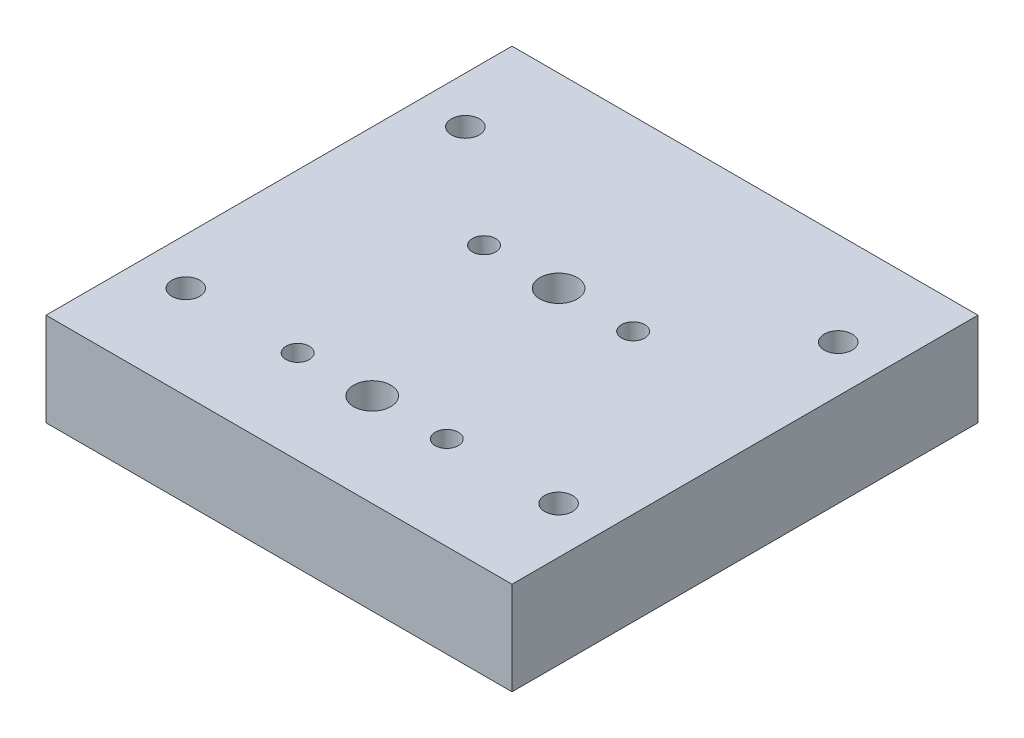
SolidWorks part; units mm, degrees
material "Сосна"
ref_plane "Спереди" through (0, 0, 0) normal (0, 0, 1) x (1, 0, 0)
ref_plane "Сверху" through (0, 0, 0) normal (0, 1, 0) x (1, 0, 0)
ref_plane "Справа" through (0, 0, 0) normal (1, 0, 0) x (0, 0, -1)
sketch "Эскиз1" plane through (0, 0, 0) normal (0, 1, 0) x (1, 0, 0)
  line L1 (0, 0) -> (100, 0)
  line L2 (0, 0) -> (0, 100)
  line L3 (0, 100) -> (100, 100)
  line L4 (100, 0) -> (100, 100)
  dimension "D1" = 100
  dimension "D2" = 100
extrude "Бобышка-Вытянуть1" add sketch "Эскиз1" along normal blind 20
sketch "Эскиз2" plane through (0, 20, 0) normal (0, 1, 0) x (1, 0, 0)
  line L0 (10, 100) -> (10, 0) construction
  line L1 (100, 100) -> (0, 100) construction
  line L2 (0, 0) -> (100, 0) construction
  line L3 (90, 100) -> (90, 0) construction
  line L4 (50, 100) -> (50, 0) construction
  line L5 (0, 100) -> (0, 0) construction
  line L6 (100, 0) -> (100, 100) construction
  line L7 (28.3008, 20) -> (77.5601, 20) construction
  line L8 (24.6726, 60) -> (70.7224, 60) construction
  circle A0 centre (10, 80) radius 3
  circle A1 centre (90, 80) radius 3
  circle A2 centre (34, 60) radius 2.5
  circle A3 centre (50, 20) radius 4
  circle A4 centre (66, 60) radius 2.5
  circle A5 centre (10, 20) radius 3
  circle A6 centre (50, 60) radius 4
  circle A7 centre (90, 20) radius 3
  circle A8 centre (34, 20) radius 2.5
  circle A9 centre (66, 20) radius 2.5
  point P40 (60.8147, 13.1244)
  dimension "D3" = 20
  dimension "D4" = 20
  dimension "D7" = 6
  dimension "D8" = 5
  dimension "D9" = 6
  dimension "D10" = 6
  dimension "D11" = 5
  dimension "D12" = 6
  dimension "D13" = 80
  dimension "D15" = 8
  dimension "D16" = 8
  dimension "D17" = 5
  dimension "D18" = 5
  dimension "D1" = 10
  dimension "D2" = 10
  dimension "D5" = 20
  dimension "D6" = 20
  dimension "D14" = 40
  dimension "D19" = 16
  dimension "D20" = 16
  dimension "D21" = 16
  dimension "D22" = 16
extrude "Вырез-Вытянуть1" cut sketch "Эскиз2" against normal blind 20
